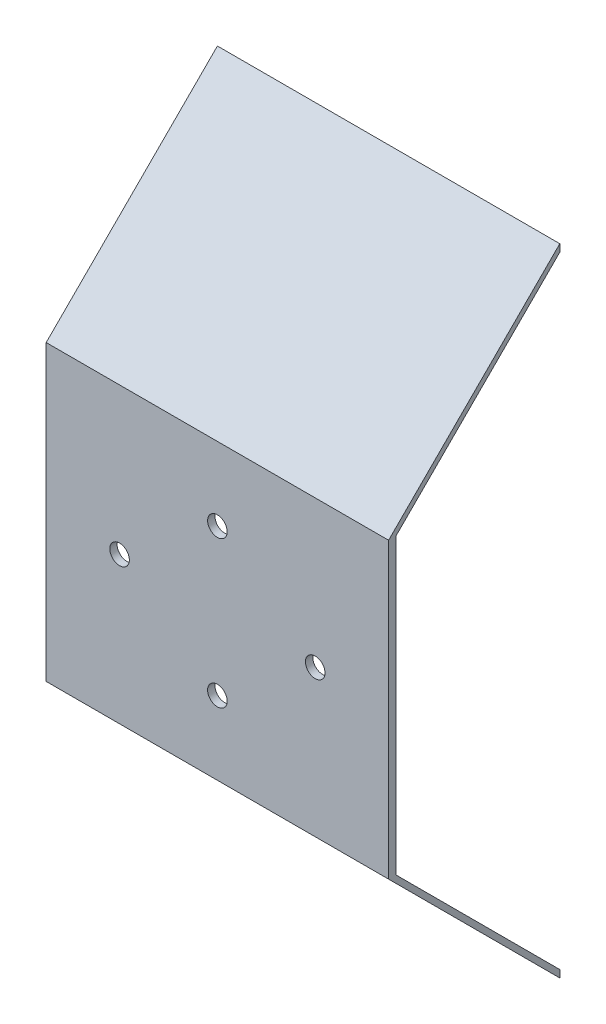
SolidWorks part; units mm, degrees
material "1023 Carbon Steel Sheet (SS)"
ref_plane "Front Plane" through (0, 0, 0) normal (1, 0, 0) x (0, 1, 0)
ref_plane "Top Plane" through (0, 0, 0) normal (0, 0, 1) x (0, 1, 0)
ref_plane "Right Plane" through (0, 0, 0) normal (0, 1, 0) x (-1, 0, 0)
sketch "Sketch1" plane through (0, 0, 0) normal (1, 0, 0) x (0, 1, 0)
  line L0 (60, 0) -> (-60, 0)
  line L1 (-60, 0) -> (-127, -67)
  line L2 (-127, -67) -> (-130, -67)
  line L3 (-130, -67) -> (-60, 3)
  line L4 (-60, 3) -> (60, 3)
  line L5 (0, 0) -> (0, 29.625) construction
  line L6 (127, -67) -> (130, -67)
  line L7 (60, 0) -> (127, -67)
  line L8 (130, -67) -> (60, 3)
  point P12 (0, 3)
  dimension "D1" = 3
  dimension "D2" = 120
  dimension "D3" = 70
  dimension "D4" = 135
  dimension "D5" = 3
extrude "Boss-Extrude1" add sketch "Sketch1" along normal blind 140
sketch "Sketch2" plane through (0, 0, 0) normal (0, 0, -1) x (1, 0, 0)
  line L2 (140, 60) -> (140, -60) construction
  line L3 (140, 60) -> (0, 60) construction
  line L4 (140, -60) -> (0, -60) construction
  circle A0 centre (30, 0) radius 4
  circle A1 centre (110, 0) radius 4
  circle A2 centre (70, 30) radius 4
  circle A3 centre (70, -30) radius 4
  dimension "D1" = 8
  dimension "D2" = 8
  dimension "D3" = 8
  dimension "D4" = 8
  dimension "D5" = 70
  dimension "D6" = 30
  dimension "D7" = 30
  dimension "D8" = 30
  dimension "D9" = 30
extrude "Cut-Extrude1" cut sketch "Sketch2" against normal blind 10
